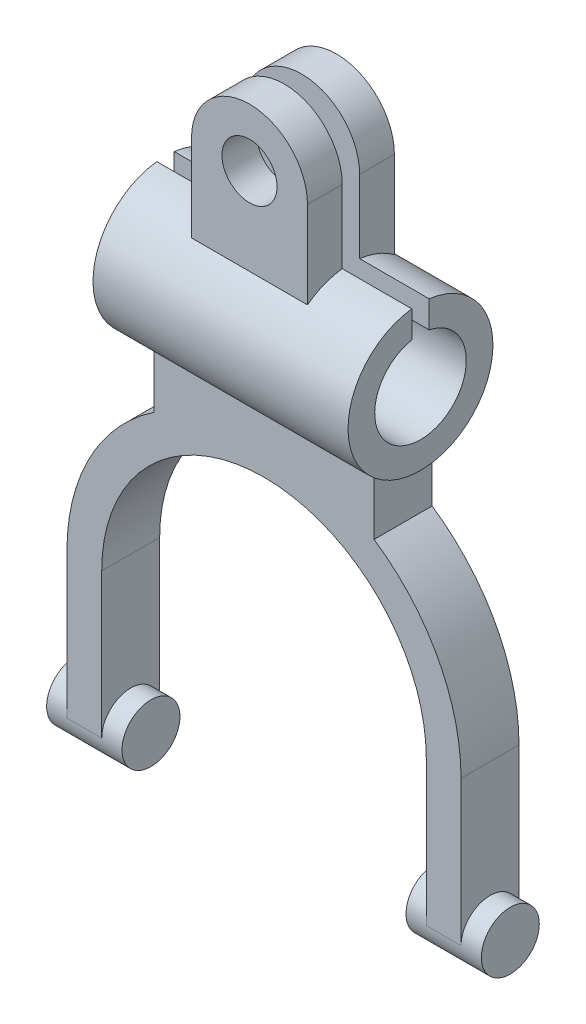
SolidWorks part; units mm, degrees
ref_plane "Front Plane" through (0, 0, 0) normal (0, 0, 1) x (1, 0, 0)
ref_plane "Top Plane" through (0, 0, 0) normal (0, 1, 0) x (1, 0, 0)
ref_plane "Right Plane" through (0, 0, 0) normal (1, 0, 0) x (0, 0, -1)
sketch "Sketch1" plane through (0, 0, 0) normal (1, 0, 0) x (0, 0, -1)
  circle A0 centre (0, 0) radius 12.5
  dimension "D1" = 25
extrude "Boss-Extrude1" add sketch "Sketch1" along normal mid plane 44
sketch "Sketch2" plane through (0, 0, 0) normal (0, 0, 1) x (1, 0, 0)
  line L0 (-10, 25) -> (-10, 0)
  line L1 (-10, 0) -> (10, 0)
  line L2 (10, 0) -> (10, 25)
  arc A0 (10, 25) -> (-10, 25) centre (0, 25) ccw
  circle A1 centre (0, 25) radius 4.75
  dimension "D1" = 20
  dimension "D3" = 9.5
  dimension "D2" = 25
extrude "Boss-Extrude2" add sketch "Sketch2" along normal mid plane 15
sketch "Sketch3" plane through (0, 0, 0) normal (0, 0, 1) x (1, 0, 0)
  line L0 (-28, -50) -> (-28, -75)
  line L1 (28, -50) -> (28, -75)
  line L2 (-19, -8.5) -> (19, -8.5)
  line L3 (0, 0) -> (0, -8.5) construction
  line L4 (-22, -12.5) -> (22, -12.5) construction
  line L5 (34, -50) -> (34, -75)
  line L6 (-34, -50) -> (-34, -75)
  line L7 (28, -75) -> (34, -75)
  line L8 (-28, -75) -> (-34, -75)
  line L9 (-19, -8.5) -> (-19, -21.8043)
  line L10 (19, -8.5) -> (19, -21.8043)
  arc A0 (28, -50) -> (-28, -50) centre (0, -50) ccw
  arc A1 (34, -50) -> (19, -21.8043) centre (0, -50) ccw
  arc A2 (-19, -21.8043) -> (-34, -50) centre (0, -50) ccw
  arc A4 (34, -50) -> (-34, -50) centre (0, -50) ccw construction
  dimension "D1" = 56
  dimension "D2" = 50
  dimension "D3" = 25
  dimension "D4" = 38
  dimension "D5" = 4
  dimension "D6" = 6
extrude "Boss-Extrude3" add sketch "Sketch3" along normal mid plane 10
sketch "Sketch4" plane through (22, 0, 0) normal (1, 0, 0) x (0, 0, -1)
  line L0 (-1.5, 0) -> (1.5, 0)
  line L1 (-1.5, 0) -> (-1.5, 38)
  line L2 (-1.5, 38) -> (1.5, 38)
  line L3 (1.5, 38) -> (1.5, 0)
  line L4 (7.5, 35) -> (-7.5, 35) construction
  circle A0 centre (0, 0) radius 7.9
  point P6 (0, 0)
  circle M1 centre (0, 0) radius 12.5
  dimension "D1" = 15.8
  dimension "D2" = 3
  dimension "D3" = 3
sketch "Sketch5" plane through (34, 0, 0) normal (1, 0, 0) x (0, 0, -1)
  circle A0 centre (0, -75) radius 5
  point P2 (0, 0)
  dimension "D1" = 75
  dimension "D2" = 10
extrude "Boss-Extrude4" add sketch "Sketch5" along normal blind 3.5 and the other way blind 9.5
mirror "Mirror1" about plane through (0, 0, 0) normal (1, 0, 0) of "Boss-Extrude4"
extrude "Cut-Extrude1" cut sketch "Sketch4" against normal through all contours L1 A0 L3 L0 | L3 A0 L1 L0 | L3 L2 L1 M1 | A0 L3 L1 M1
